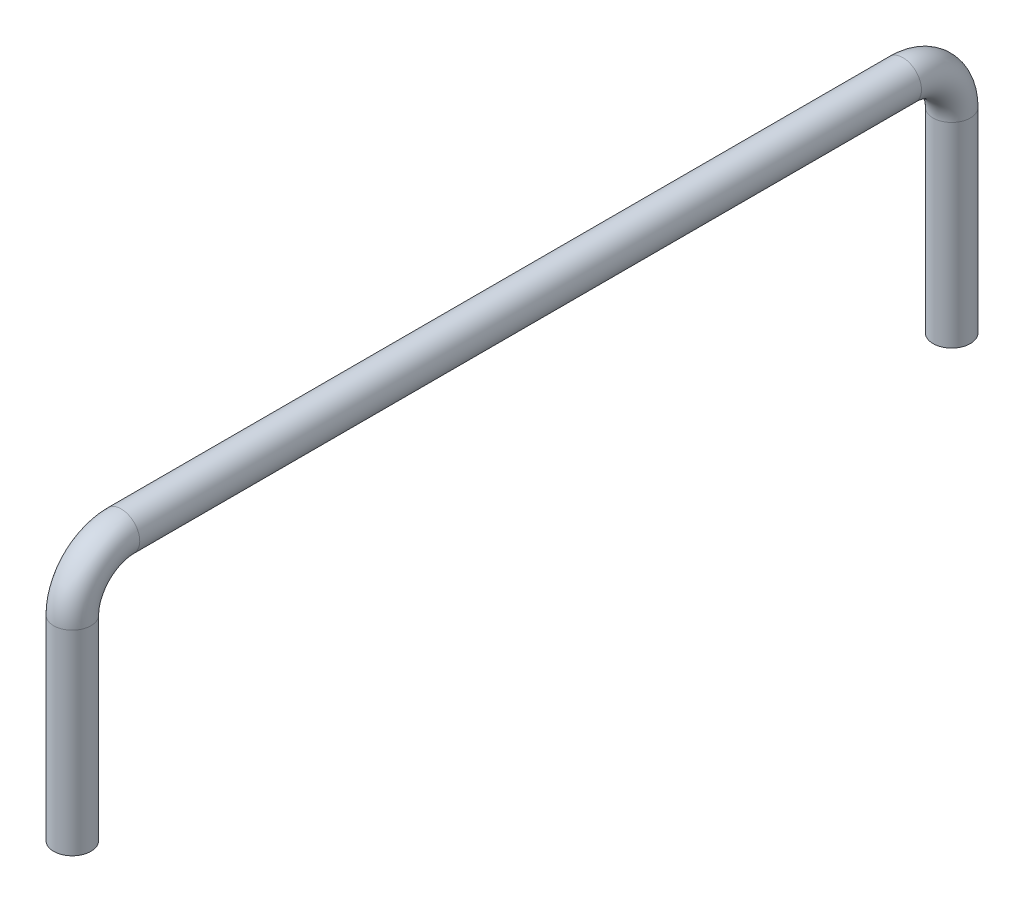
SolidWorks part; units mm, degrees
ref_plane "Front Plane" through (0, 0, 0) normal (0, 0, 1) x (1, 0, 0)
ref_plane "Top Plane" through (0, 0, 0) normal (0, 1, 0) x (1, 0, 0)
ref_plane "Right Plane" through (0, 0, 0) normal (1, 0, 0) x (0, 0, -1)
sketch "Sketch2" plane through (0, 0, 0) normal (0, 1, 0) x (1, 0, 0)
  circle A0 centre (0, 0) radius 0.381
  dimension "D1" = 0.762
sketch "Sketch3" plane through (0, 0, 0) normal (1, 0, 0) x (0, 0, -1)
  line L0 (0, 0) -> (0, 4)
  line L1 (0.381, 0) -> (-0.381, 0) construction
  line L2 (1, 5) -> (17, 5)
  line L3 (18, 4) -> (18, 0)
  arc A0 (0, 4) -> (1, 5) centre (1, 4) cw
  arc A1 (17, 5) -> (18, 4) centre (17, 4) cw
  dimension "D2" = 1
  dimension "D1" = 4
  dimension "D3" = 16
sweep "Sweep1" add profiles "Sketch2" path "Sketch3"
